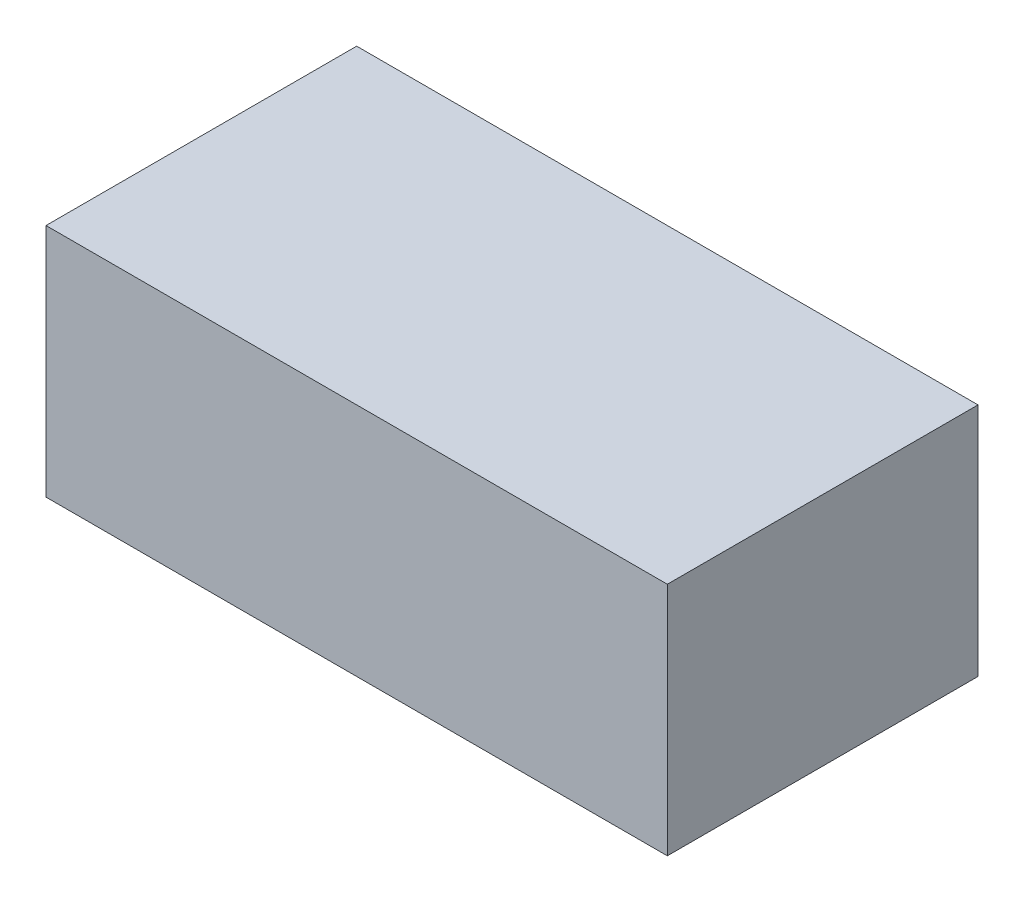
SolidWorks part; units mm, degrees
ref_plane "前视基准面" through (0, 0, 0) normal (0, 0, 1) x (1, 0, 0)
ref_plane "上视基准面" through (0, 0, 0) normal (0, 1, 0) x (1, 0, 0)
ref_plane "右视基准面" through (0, 0, 0) normal (1, 0, 0) x (0, 0, -1)
sketch "草图1" plane through (0, 0, 0) normal (0, 1, 0) x (1, 0, 0)
  line L1 (-70, -35) -> (70, -35)
  line L2 (-70, -35) -> (-70, 35)
  line L3 (-70, 35) -> (70, 35)
  line L4 (70, -35) -> (70, 35)
  line L5 (-70, -35) -> (70, 35) construction
  line L6 (-70, 35) -> (70, -35) construction
  point P0 (0, 0)
  dimension "D1" = 140
  dimension "D2" = 70
extrude "凸台-拉伸1" add sketch "草图1" along normal mid plane 53
